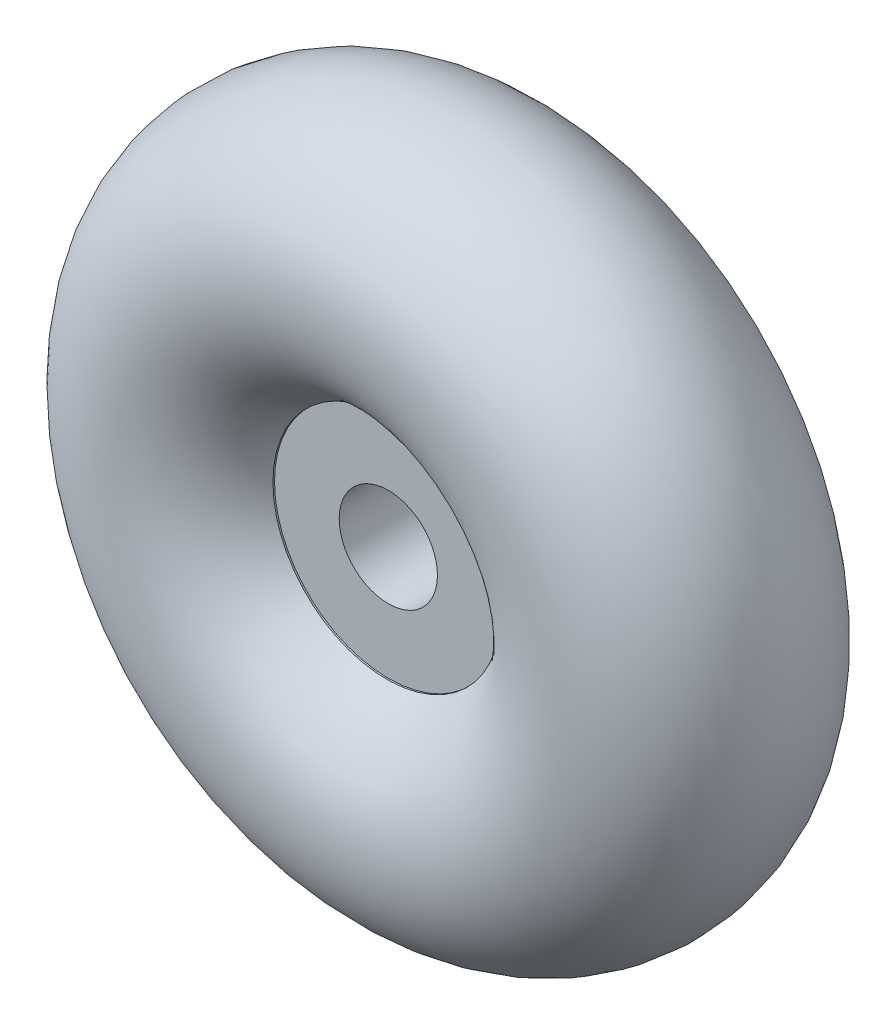
SolidWorks part; units mm, degrees
material "Силиконовая резина"
ref_plane "Спереди" through (0, 0, 0) normal (0, 0, 1) x (1, 0, 0)
ref_plane "Сверху" through (0, 0, 0) normal (0, 1, 0) x (1, 0, 0)
ref_plane "Справа" through (0, 0, 0) normal (1, 0, 0) x (0, 0, -1)
sketch "Эскиз1" plane through (0, 0, 0) normal (0, 0, 1) x (1, 0, 0)
  circle A0 centre (0, 0) radius 10
  dimension "D1" = 20
extrude "Бобышка-Вытянуть1" add sketch "Эскиз1" along normal blind 10 contours A0
sketch "Эскиз2" plane through (0, 0, 0) normal (0, 1, 0) x (1, 0, 0)
  line L0 (10, 0) -> (10, -10)
  line L1 (-10, -10) -> (-10, 0)
  line L2 (-10, -10) -> (-10, 0)
  line L3 (10, 0) -> (10, -10)
  line L4 (0, 0) -> (0, -10) construction
  arc A0 (10, -10) -> (10, 0) centre (18.6603, -5) ccw
  dimension "D1" = 10
revolve "Повернуть-Тонкостенный1" add sketch "Эскиз2" angle 360 mid plane about L4
sketch "Эскиз3" plane through (0, 0, 0) normal (0, 0, -1) x (-1, 0, 0)
  circle A0 centre (0, 0) radius 4.1
extrude "Вырез-Вытянуть1" cut sketch "Эскиз3" against normal through all
